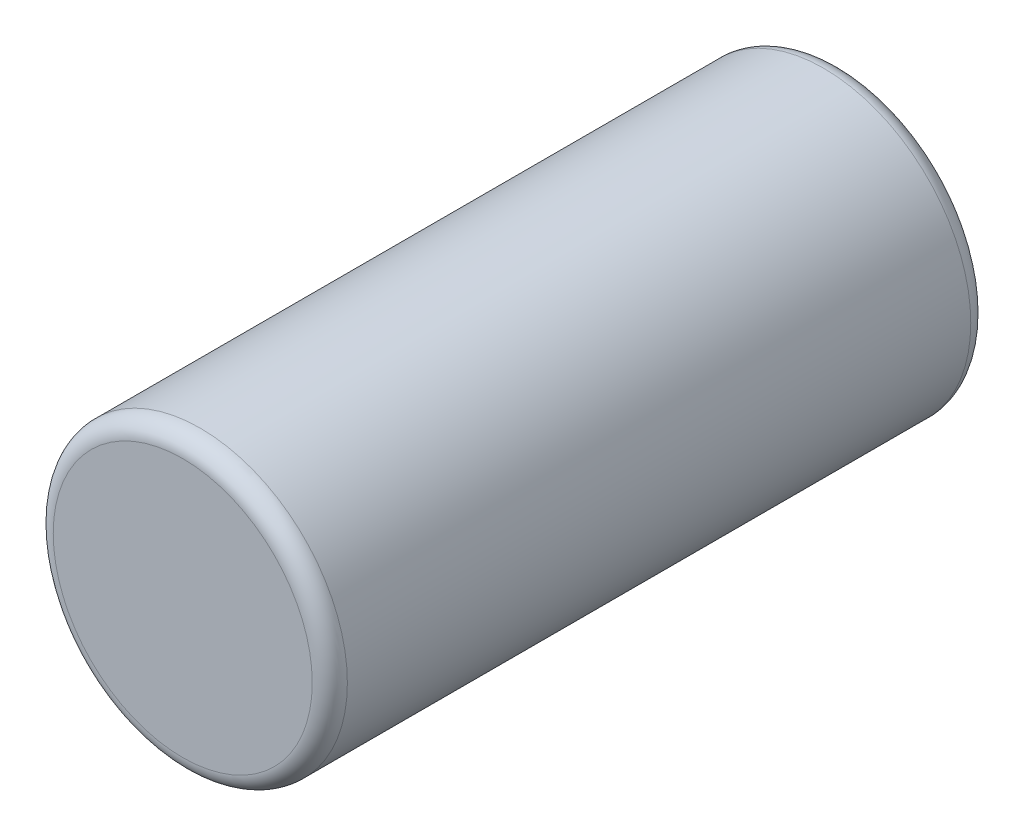
SolidWorks part; units mm, degrees
ref_plane "Front Plane" through (0, 0, 0) normal (0, 0, 1) x (1, 0, 0)
ref_plane "Top Plane" through (0, 0, 0) normal (0, 1, 0) x (1, 0, 0)
ref_plane "Right Plane" through (0, 0, 0) normal (1, 0, 0) x (0, 0, -1)
sketch "Sketch1" plane through (0, 0, 0) normal (0, 0, 1) x (1, 0, 0)
  circle A0 centre (0, 0) radius 3.35
  dimension "D1" = 6.7
extrude "Boss-Extrude1" add sketch "Sketch1" along normal blind 15
fillet "Fillet1" radius 0.4 2 edges at (3.35, 0, 0) (3.35, 0, 15)
